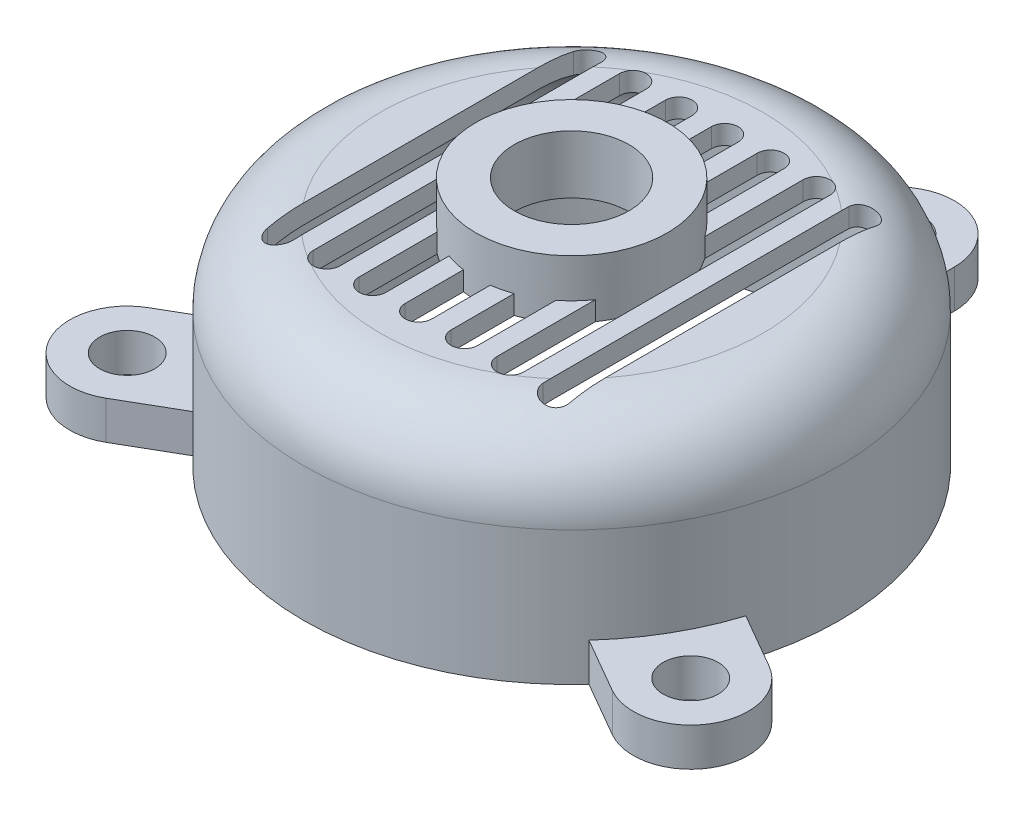
SolidWorks part; units mm, degrees
ref_plane "Front Plane" through (0, 0, 0) normal (0, 0, 1) x (1, 0, 0)
ref_plane "Top Plane" through (0, 0, 0) normal (0, 1, 0) x (1, 0, 0)
ref_plane "Right Plane" through (0, 0, 0) normal (1, 0, 0) x (0, 0, -1)
sketch "Sketch1" plane through (0, 0, 0) normal (0, 1, 0) x (1, 0, 0)
  circle A0 centre (0, 0) radius 87.5
  point P2 (0, 0)
  dimension "D1" = 175
extrude "Boss-Extrude1" add sketch "Sketch1" along normal blind 68.75
fillet "Fillet1" radius 25 1 edges at (0, 68.75, 87.5)
shell "Shell1" thickness 6.25
sketch "Sketch2" plane through (0, 68.75, 0) normal (0, 1, 0) x (1, 0, 0)
  line L0 (-34.375, -50) -> (-34.375, 50)
  line L2 (-49.375, -50) -> (-49.375, 50)
  line L4 (-40.625, -50) -> (-40.625, 50)
  line L5 (-49.375, -50) -> (-40.625, 50) construction
  line L6 (-49.375, 50) -> (-40.625, -50) construction
  line L7 (-25.625, -50) -> (-25.625, 50)
  line L8 (-34.375, -50) -> (-25.625, 50) construction
  line L9 (-34.375, 50) -> (-25.625, -50) construction
  line L10 (-19.375, -50) -> (-19.375, 50)
  line L11 (-10.625, -50) -> (-10.625, 50)
  line L12 (-19.375, -50) -> (-10.625, 50) construction
  line L13 (-19.375, 50) -> (-10.625, -50) construction
  line L14 (-4.375, -50) -> (-4.375, 50)
  line L15 (4.375, -50) -> (4.375, 50)
  line L16 (-4.375, -50) -> (4.375, 50) construction
  line L17 (-4.375, 50) -> (4.375, -50) construction
  line L18 (10.625, -50) -> (10.625, 50)
  line L19 (19.375, -50) -> (19.375, 50)
  line L20 (10.625, -50) -> (19.375, 50) construction
  line L21 (10.625, 50) -> (19.375, -50) construction
  line L22 (25.625, -50) -> (25.625, 50)
  line L23 (34.375, -50) -> (34.375, 50)
  line L24 (25.625, -50) -> (34.375, 50) construction
  line L25 (25.625, 50) -> (34.375, -50) construction
  line L26 (40.625, -50) -> (40.625, 50)
  line L27 (49.375, -50) -> (49.375, 50)
  line L28 (40.625, -50) -> (49.375, 50) construction
  line L29 (40.625, 50) -> (49.375, -50) construction
  arc A0 (-40.625, 50) -> (-49.375, 50) centre (-45, 50) ccw
  arc A1 (-40.625, -50) -> (-49.375, -50) centre (-45, -50) cw
  arc A2 (-25.625, 50) -> (-34.375, 50) centre (-30, 50) ccw
  arc A3 (-25.625, -50) -> (-34.375, -50) centre (-30, -50) cw
  arc A4 (-10.625, 50) -> (-19.375, 50) centre (-15, 50) ccw
  arc A5 (-10.625, -50) -> (-19.375, -50) centre (-15, -50) cw
  arc A6 (4.375, 50) -> (-4.375, 50) centre (0, 50) ccw
  arc A7 (4.375, -50) -> (-4.375, -50) centre (0, -50) cw
  arc A8 (19.375, 50) -> (10.625, 50) centre (15, 50) ccw
  arc A9 (19.375, -50) -> (10.625, -50) centre (15, -50) cw
  arc A10 (34.375, 50) -> (25.625, 50) centre (30, 50) ccw
  arc A11 (34.375, -50) -> (25.625, -50) centre (30, -50) cw
  arc A12 (49.375, 50) -> (40.625, 50) centre (45, 50) ccw
  arc A13 (49.375, -50) -> (40.625, -50) centre (45, -50) cw
  point P0 (-45, 0)
  point P5 (-40.625, 0)
  point P9 (-30, 0)
  point P17 (-15, 0)
  point P24 (0, 0)
  point P31 (15, 0)
  point P38 (30, 0)
  point P45 (45, 0)
  dimension "D1" = 100
  dimension "D2" = 8.75
  dimension "D3" = 7
extrude "Cut-Extrude1" cut sketch "Sketch2" against normal blind 68.75
sketch "Sketch3" plane through (0, 68.75, 0) normal (0, 1, 0) x (1, 0, 0)
  circle A0 centre (0, 0) radius 18.75
  circle A1 centre (0, 0) radius 31.25
  dimension "D1" = 62.5
  dimension "D2" = 37.5
extrude "Boss-Extrude2" add sketch "Sketch3" along normal blind 12.75 and the other way blind 6.25
sketch "Sketch4" plane through (0, 62.5, 0) normal (0, -1, 0) x (1, 0, 0)
  circle A0 centre (0, 0) radius 18.75
extrude "Cut-Extrude2" cut sketch "Sketch4" against normal blind 12.75
sketch "Sketch5" plane through (0, 0, 0) normal (0, 1, 0) x (1, 0, 0)
  line L0 (0, 0) -> (0, 133.4776) construction
  line L3 (-18.75, 106.25) -> (-18.75, 85.4675)
  line L5 (18.75, 85.4675) -> (18.75, 106.25)
  line L6 (101.3902, -36.887) -> (83.392, -26.4958)
  line L7 (64.642, -58.9717) -> (82.6402, -69.363)
  line L8 (-82.6402, -69.363) -> (-64.642, -58.9717)
  line L9 (-83.392, -26.4958) -> (-101.3902, -36.887)
  arc A0 (18.75, 85.4675) -> (-18.75, 85.4675) centre (0, 0) ccw
  circle A2 centre (0, 106.25) radius 9
  arc A3 (18.75, 106.25) -> (-18.75, 106.25) centre (0, 106.25) ccw
  arc A4 (64.642, -58.9717) -> (83.392, -26.4958) centre (0, 0) ccw
  circle A5 centre (92.0152, -53.125) radius 9
  arc A6 (82.6402, -69.363) -> (101.3902, -36.887) centre (92.0152, -53.125) ccw
  arc A7 (-83.392, -26.4958) -> (-64.642, -58.9717) centre (0, 0) ccw
  circle A8 centre (-92.0152, -53.125) radius 9
  arc A9 (-101.3902, -36.887) -> (-82.6402, -69.363) centre (-92.0152, -53.125) ccw
  point P23 (0, 0)
  dimension "D1" = 3
  dimension "D2" = 37.5
  dimension "D3" = 18
extrude "Boss-Extrude3" add sketch "Sketch5" along normal blind 12.5
